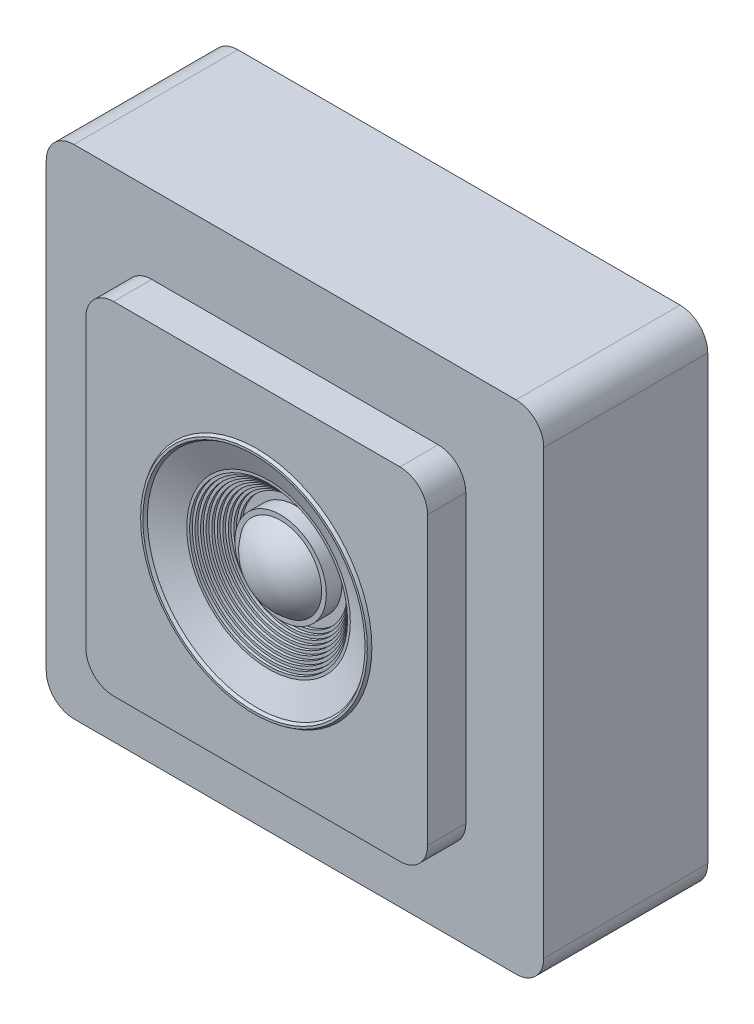
SolidWorks part; units mm, degrees
ref_plane "Front Plane" through (0, 0, 0) normal (0, 0, 1) x (1, 0, 0)
ref_plane "Top Plane" through (0, 0, 0) normal (0, 1, 0) x (1, 0, 0)
ref_plane "Right Plane" through (0, 0, 0) normal (1, 0, 0) x (0, 0, -1)
sketch "Sketch1" plane through (0, 0, 0) normal (0, 0, 1) x (1, 0, 0)
  line L0 (-18, 18) -> (18, -18) construction
  line L1 (-16, 18) -> (16, 18)
  line L2 (-18, 16) -> (-18, -16)
  line L3 (-16, -18) -> (16, -18)
  line L4 (18, 16) -> (18, -16)
  arc A0 (18, -16) -> (16, -18) centre (16, -16) cw
  arc A1 (-16, -18) -> (-18, -16) centre (-16, -16) cw
  arc A2 (-18, 16) -> (-16, 18) centre (-16, 16) cw
  arc A3 (16, 18) -> (18, 16) centre (16, 16) cw
  point P11 (-18, -18)
  point P17 (18, 18)
  dimension "D3" = 2
  dimension "D1" = 36
  dimension "D2" = 36
extrude "Boss-Extrude1" add sketch "Sketch1" along normal blind 11.8681
sketch "Sketch2" plane through (0, 0, 0) normal (0, 0, -1) x (-1, 0, 0)
  line L1 (-13.5545, 14.1979) -> (14.4455, 14.1979) construction
  line L2 (-13.5545, 14.1979) -> (-13.5545, -13.8021) construction
  line L3 (-13.5545, -13.8021) -> (14.4455, -13.8021) construction
  line L4 (14.4455, 14.1979) -> (14.4455, -13.8021) construction
  circle A0 centre (-13.5545, -13.8021) radius 1.5
  circle A1 centre (14.4455, 14.1979) radius 1.5
  dimension "D2" = 3
  dimension "D1" = 28
extrude "Cut-Extrude1" cut sketch "Sketch2" against normal blind 5
sketch "Sketch3" plane through (0, 0, 11.8681) normal (0, 0, 1) x (1, 0, 0)
  line L0 (-12.3626, 12.3626) -> (12.3626, -12.3626) construction
  line L1 (-10.3626, 12.3626) -> (10.3626, 12.3626)
  line L2 (-12.3626, 10.3626) -> (-12.3626, -10.3626)
  line L3 (-10.3626, -12.3626) -> (10.3626, -12.3626)
  line L4 (12.3626, 10.3626) -> (12.3626, -10.3626)
  arc A0 (-12.3626, -10.3626) -> (-10.3626, -12.3626) centre (-10.3626, -10.3626) ccw
  arc A1 (10.3626, -12.3626) -> (12.3626, -10.3626) centre (10.3626, -10.3626) ccw
  arc A2 (12.3626, 10.3626) -> (10.3626, 12.3626) centre (10.3626, 10.3626) ccw
  arc A3 (-10.3626, 12.3626) -> (-12.3626, 10.3626) centre (-10.3626, 10.3626) ccw
  point P6 (-12.3626, -12.3626)
  dimension "D2" = 2
  dimension "D1" = 24.7253
extrude "Boss-Extrude2" add sketch "Sketch3" along normal blind 2.7692
sketch "Sketch4" plane through (0, 0, 0) normal (0, 1, 0) x (1, 0, 0)
  line L0 (-8.3314, -14.6374) -> (-8.2027, -14.8374)
  line L1 (-8.2027, -14.8374) -> (-8.0408, -14.8374)
  line L2 (-8.0408, -14.8374) -> (-7.9121, -14.6374)
  line L3 (-8.3314, -14.6374) -> (-7.9121, -14.6374)
  line L4 (-7.9121, -14.6374) -> (-7.9121, -15.6124)
  line L5 (0, -15.4762) -> (0, -15.957) construction
  line L7 (-12.3626, -14.6374) -> (-10.3626, -14.6374) construction
  dimension "D1" = 15.8242
  dimension "D2" = 0.2
revolve "Revolve1" add sketch "Sketch4" angle 360 about L5
sketch "Sketch5" plane through (0, 0, 0) normal (0, 1, 0) x (1, 0, 0)
  line L0 (-7.9121, -14.6374) -> (-5.9185, -13.7821)
  line L2 (0, -11.7821) -> (0, -14.6374)
  line L3 (0, -14.6374) -> (-7.9121, -14.6374)
  line L4 (0, -19.1463) -> (0, -14.2818) construction
  line L5 (-4.9185, -12.7821) -> (-4.7185, -12.7821)
  line L6 (-7.9121, -14.6374) -> (7.9121, -14.6374) construction
  line L7 (-4.7185, -12.7821) -> (-4.7185, -12.5821)
  line L8 (-4.7185, -12.5821) -> (-4.5185, -12.5821)
  line L9 (-5.9185, -13.7821) -> (-5.7185, -13.7821)
  line L10 (-5.7185, -13.7821) -> (-5.7185, -13.5821)
  line L11 (-5.7185, -13.5821) -> (-5.5185, -13.5821)
  line L12 (-5.5185, -13.5821) -> (-5.5185, -13.3821)
  line L13 (-5.5185, -13.3821) -> (-5.3185, -13.3821)
  line L14 (-5.3185, -13.3821) -> (-5.3185, -13.1821)
  line L15 (-5.3185, -13.1821) -> (-5.1185, -13.1821)
  line L16 (-5.1185, -13.1821) -> (-5.1185, -12.9821)
  line L17 (-5.1185, -12.9821) -> (-4.9185, -12.9821)
  line L18 (-4.9185, -12.9821) -> (-4.9185, -12.7821)
  line L19 (-4.5185, -12.5821) -> (-4.5185, -12.3821)
  line L20 (-4.5185, -12.3821) -> (-4.3185, -12.3821)
  line L21 (-4.3185, -12.3821) -> (-4.3185, -12.1821)
  line L22 (-4.3185, -12.1821) -> (-4.1185, -12.1821)
  line L23 (-4.1185, -12.1821) -> (-4.1185, -11.9821)
  line L24 (-4.1185, -11.9821) -> (-3.9185, -11.9821)
  line L25 (-3.9185, -11.9821) -> (-3.9185, -11.7821)
  line L26 (-3.9185, -11.7821) -> (0, -11.7821)
  dimension "D1" = 0.2
  dimension "D2" = 0.2
revolve "Cut-Revolve1" cut sketch "Sketch5" angle 360 about L4
sketch "Sketch6" plane through (0, 0, 0) normal (0, 1, 0) x (1, 0, 0)
  line L0 (-3.3083, -11.7821) -> (-3.3083, -12.9084)
  line L1 (-3.3083, -12.9084) -> (-2.9631, -12.9084)
  line L2 (0, -14.4526) -> (0, -11.7821)
  line L3 (-3.3083, -11.7821) -> (0, -11.7821)
  line L4 (0, 199984.5238) -> (0, -200015.957) construction
  line L5 (-3.9185, -11.7821) -> (3.9185, -11.7821) construction
  arc A0 (-2.9631, -12.9084) -> (0, -14.4526) centre (0, -10.8378) ccw
revolve "Revolve2" add sketch "Sketch6" angle 360 about L2
sketch "Sketch7" plane through (0, 0, 0) normal (0, 0, -1) x (-1, 0, 0)
  line L0 (18, 16) -> (18, -16) construction
  line L1 (2.5769, -10.6286) -> (11.0769, -10.6286)
  line L2 (2.5769, -10.6286) -> (2.5769, -15.4286)
  line L3 (2.5769, -15.4286) -> (11.0769, -15.4286)
  line L4 (11.0769, -10.6286) -> (11.0769, -15.4286)
  line L5 (16, -18) -> (-16, -18) construction
  line L6 (4.3147, -12.285) -> (5.6562, -12.285) construction
  line L7 (3.8147, -12.035) -> (4.3147, -12.035)
  line L8 (3.8147, -12.035) -> (3.8147, -12.535)
  line L9 (3.8147, -12.535) -> (4.3147, -12.535)
  line L10 (4.3147, -12.035) -> (4.3147, -12.535)
  line L11 (5.6562, -12.035) -> (6.1562, -12.035)
  line L12 (5.6562, -12.035) -> (5.6562, -12.535)
  line L13 (5.6562, -12.535) -> (6.1562, -12.535)
  line L14 (6.1562, -12.035) -> (6.1562, -12.535)
  line L15 (7.4977, -12.035) -> (7.9977, -12.035)
  line L16 (7.4977, -12.035) -> (7.4977, -12.535)
  line L17 (7.4977, -12.535) -> (7.9977, -12.535)
  line L18 (7.9977, -12.035) -> (7.9977, -12.535)
  line L19 (9.3391, -12.035) -> (9.8391, -12.035)
  line L20 (9.3391, -12.035) -> (9.3391, -12.535)
  line L21 (9.3391, -12.535) -> (9.8391, -12.535)
  line L22 (9.8391, -12.035) -> (9.8391, -12.535)
  line L23 (6.1562, -12.285) -> (7.4977, -12.285) construction
  line L24 (7.9977, -12.285) -> (9.3391, -12.285) construction
  line L25 (6.8269, -12.285) -> (6.8269, -15.4286) construction
  point P30 (0, 0)
  point P31 (0, 0)
  point P32 (0, 0)
  point P33 (5.6224, -11.7131)
  point P34 (2.6896, -12.6287)
  point P35 (0, 0)
  point P36 (6.8269, -12.9644)
  point P39 (0, 0)
  point P40 (6.8269, -12.3684)
  point P41 (5.6562, -12.285)
  dimension "D1" = 4.8
  dimension "D2" = 8.5
  dimension "D3" = 6.9231
  dimension "D4" = 2.5714
  dimension "D5" = 0.5
extrude "Cut-Extrude2" cut sketch "Sketch7" against normal blind 10
equation "\"D1@Sketch3\"=125*36/182"
equation "\"D1@Sketch4\"=80*36/182"
